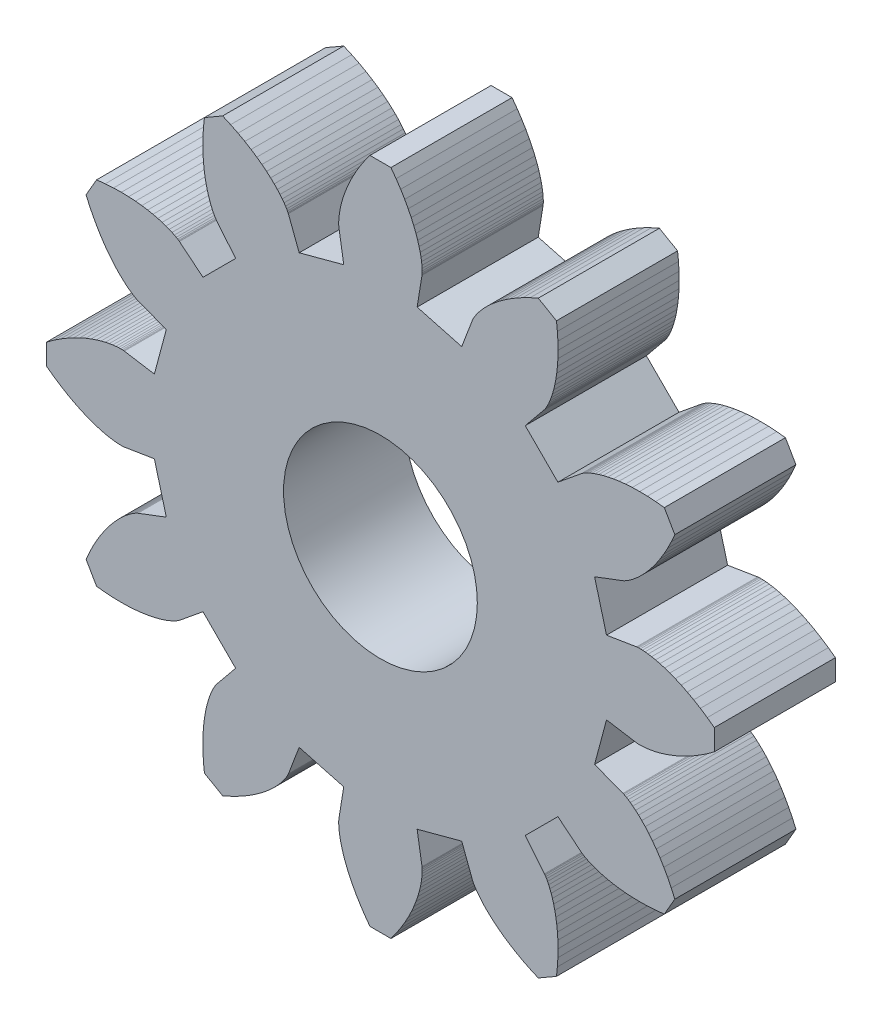
SolidWorks part; units mm, degrees
ref_plane "Front Plane" through (0, 0, 0) normal (0, 0, 1) x (1, 0, 0)
ref_plane "Top Plane" through (0, 0, 0) normal (0, 1, 0) x (1, 0, 0)
ref_plane "Right Plane" through (0, 0, 0) normal (1, 0, 0) x (0, 0, -1)
sketch "Model" plane through (0, 0, 0) normal (0, 0, 1) x (1, 0, 0)
  line L0 (9.3334, 1.5146) -> (10.5736, 1.7159)
  line L1 (10.5736, 1.7159) -> (10.5833, 1.7172)
  line L2 (10.5833, 1.7172) -> (10.6124, 1.7199)
  line L3 (10.6124, 1.7199) -> (10.6611, 1.7225)
  line L4 (10.6611, 1.7225) -> (10.7293, 1.7232)
  line L5 (10.7293, 1.7232) -> (10.817, 1.7204)
  line L6 (10.817, 1.7204) -> (10.9239, 1.7124)
  line L7 (10.9239, 1.7124) -> (11.0498, 1.6976)
  line L8 (11.0498, 1.6976) -> (11.1941, 1.6744)
  line L9 (11.1941, 1.6744) -> (11.3565, 1.6411)
  line L10 (11.3565, 1.6411) -> (11.5362, 1.5962)
  line L11 (11.5362, 1.5962) -> (11.7325, 1.5382)
  line L12 (11.7325, 1.5382) -> (11.9446, 1.4655)
  line L13 (11.9446, 1.4655) -> (12.1716, 1.3768)
  line L14 (12.1716, 1.3768) -> (12.4124, 1.2706)
  line L15 (12.4124, 1.2706) -> (12.6659, 1.1456)
  line L16 (12.6659, 1.1456) -> (12.931, 1.0006)
  line L17 (12.931, 1.0006) -> (13.2064, 0.8343)
  line L18 (13.2064, 0.8343) -> (13.4907, 0.6456)
  line L19 (13.4907, 0.6456) -> (13.7824, 0.4335)
  line L20 (13.7824, 0.4335) -> (13.7824, -0.4335)
  line L21 (13.7824, -0.4335) -> (13.4907, -0.6456)
  line L22 (13.4907, -0.6456) -> (13.2064, -0.8343)
  line L23 (13.2064, -0.8343) -> (12.931, -1.0006)
  line L24 (12.931, -1.0006) -> (12.6659, -1.1456)
  line L25 (12.6659, -1.1456) -> (12.4124, -1.2706)
  line L26 (12.4124, -1.2706) -> (12.1716, -1.3768)
  line L27 (12.1716, -1.3768) -> (11.9446, -1.4655)
  line L28 (11.9446, -1.4655) -> (11.7325, -1.5382)
  line L29 (11.7325, -1.5382) -> (11.5362, -1.5962)
  line L30 (11.5362, -1.5962) -> (11.3565, -1.6411)
  line L31 (11.3565, -1.6411) -> (11.1941, -1.6744)
  line L32 (11.1941, -1.6744) -> (11.0498, -1.6976)
  line L33 (11.0498, -1.6976) -> (10.9239, -1.7124)
  line L34 (10.9239, -1.7124) -> (10.817, -1.7204)
  line L35 (10.817, -1.7204) -> (10.7293, -1.7232)
  line L36 (10.7293, -1.7232) -> (10.6611, -1.7225)
  line L37 (10.6611, -1.7225) -> (10.6124, -1.7199)
  line L38 (10.6124, -1.7199) -> (10.5833, -1.7172)
  line L39 (10.5833, -1.7172) -> (10.5736, -1.7159)
  line L40 (10.5736, -1.7159) -> (9.3334, -1.5146)
  line L41 (9.3334, -1.5146) -> (8.8402, -3.355)
  line L42 (8.8402, -3.355) -> (10.015, -3.8008)
  line L43 (10.015, -3.8008) -> (10.024, -3.8045)
  line L44 (10.024, -3.8045) -> (10.0506, -3.8167)
  line L45 (10.0506, -3.8167) -> (10.094, -3.8388)
  line L46 (10.094, -3.8388) -> (10.1535, -3.8723)
  line L47 (10.1535, -3.8723) -> (10.228, -3.9186)
  line L48 (10.228, -3.9186) -> (10.3166, -3.979)
  line L49 (10.3166, -3.979) -> (10.4182, -4.0547)
  line L50 (10.4182, -4.0547) -> (10.5316, -4.147)
  line L51 (10.5316, -4.147) -> (10.6556, -4.257)
  line L52 (10.6556, -4.257) -> (10.7887, -4.3857)
  line L53 (10.7887, -4.3857) -> (10.9297, -4.5341)
  line L54 (10.9297, -4.5341) -> (11.0771, -4.7031)
  line L55 (11.0771, -4.7031) -> (11.2293, -4.8934)
  line L56 (11.2293, -4.8934) -> (11.3847, -5.1058)
  line L57 (11.3847, -5.1058) -> (11.5418, -5.3408)
  line L58 (11.5418, -5.3408) -> (11.6989, -5.599)
  line L59 (11.6989, -5.599) -> (11.8542, -5.8807)
  line L60 (11.8542, -5.8807) -> (12.0061, -6.1862)
  line L61 (12.0061, -6.1862) -> (12.1527, -6.5158)
  line L62 (12.1527, -6.5158) -> (11.7192, -7.2667)
  line L63 (11.7192, -7.2667) -> (11.3605, -7.3044)
  line L64 (11.3605, -7.3044) -> (11.0199, -7.3257)
  line L65 (11.0199, -7.3257) -> (10.6983, -7.332)
  line L66 (10.6983, -7.332) -> (10.3962, -7.3251)
  line L67 (10.3962, -7.3251) -> (10.1141, -7.3066)
  line L68 (10.1141, -7.3066) -> (9.8525, -7.2781)
  line L69 (9.8525, -7.2781) -> (9.6115, -7.2415)
  line L70 (9.6115, -7.2415) -> (9.3915, -7.1984)
  line L71 (9.3915, -7.1984) -> (9.1925, -7.1505)
  line L72 (9.1925, -7.1505) -> (9.0144, -7.0995)
  line L73 (9.0144, -7.0995) -> (8.8572, -7.0472)
  line L74 (8.8572, -7.0472) -> (8.7206, -6.9951)
  line L75 (8.7206, -6.9951) -> (8.6042, -6.945)
  line L76 (8.6042, -6.945) -> (8.5076, -6.8984)
  line L77 (8.5076, -6.8984) -> (8.4303, -6.857)
  line L78 (8.4303, -6.857) -> (8.3715, -6.8223)
  line L79 (8.3715, -6.8223) -> (8.3307, -6.7957)
  line L80 (8.3307, -6.7957) -> (8.3068, -6.7787)
  line L81 (8.3068, -6.7787) -> (8.2991, -6.7728)
  line L82 (8.2991, -6.7728) -> (7.3256, -5.9784)
  line L83 (7.3256, -5.9784) -> (5.9784, -7.3256)
  line L84 (5.9784, -7.3256) -> (6.7728, -8.2991)
  line L85 (6.7728, -8.2991) -> (6.7787, -8.3068)
  line L86 (6.7787, -8.3068) -> (6.7957, -8.3307)
  line L87 (6.7957, -8.3307) -> (6.8223, -8.3715)
  line L88 (6.8223, -8.3715) -> (6.857, -8.4303)
  line L89 (6.857, -8.4303) -> (6.8984, -8.5076)
  line L90 (6.8984, -8.5076) -> (6.945, -8.6042)
  line L91 (6.945, -8.6042) -> (6.9951, -8.7206)
  line L92 (6.9951, -8.7206) -> (7.0472, -8.8572)
  line L93 (7.0472, -8.8572) -> (7.0995, -9.0144)
  line L94 (7.0995, -9.0144) -> (7.1505, -9.1925)
  line L95 (7.1505, -9.1925) -> (7.1984, -9.3915)
  line L96 (7.1984, -9.3915) -> (7.2415, -9.6115)
  line L97 (7.2415, -9.6115) -> (7.2781, -9.8525)
  line L98 (7.2781, -9.8525) -> (7.3066, -10.1141)
  line L99 (7.3066, -10.1141) -> (7.3251, -10.3962)
  line L100 (7.3251, -10.3962) -> (7.332, -10.6983)
  line L101 (7.332, -10.6983) -> (7.3257, -11.0199)
  line L102 (7.3257, -11.0199) -> (7.3044, -11.3605)
  line L103 (7.3044, -11.3605) -> (7.2667, -11.7192)
  line L104 (7.2667, -11.7192) -> (6.5158, -12.1527)
  line L105 (6.5158, -12.1527) -> (6.1862, -12.0061)
  line L106 (6.1862, -12.0061) -> (5.8807, -11.8542)
  line L107 (5.8807, -11.8542) -> (5.599, -11.6989)
  line L108 (5.599, -11.6989) -> (5.3408, -11.5418)
  line L109 (5.3408, -11.5418) -> (5.1058, -11.3847)
  line L110 (5.1058, -11.3847) -> (4.8934, -11.2293)
  line L111 (4.8934, -11.2293) -> (4.7031, -11.0771)
  line L112 (4.7031, -11.0771) -> (4.5341, -10.9297)
  line L113 (4.5341, -10.9297) -> (4.3857, -10.7887)
  line L114 (4.3857, -10.7887) -> (4.257, -10.6556)
  line L115 (4.257, -10.6556) -> (4.147, -10.5316)
  line L116 (4.147, -10.5316) -> (4.0547, -10.4182)
  line L117 (4.0547, -10.4182) -> (3.979, -10.3166)
  line L118 (3.979, -10.3166) -> (3.9186, -10.228)
  line L119 (3.9186, -10.228) -> (3.8723, -10.1535)
  line L120 (3.8723, -10.1535) -> (3.8388, -10.094)
  line L121 (3.8388, -10.094) -> (3.8167, -10.0506)
  line L122 (3.8167, -10.0506) -> (3.8045, -10.024)
  line L123 (3.8045, -10.024) -> (3.8008, -10.015)
  line L124 (3.8008, -10.015) -> (3.355, -8.8402)
  line L125 (3.355, -8.8402) -> (1.5146, -9.3334)
  line L126 (1.5146, -9.3334) -> (1.7159, -10.5736)
  line L127 (1.7159, -10.5736) -> (1.7172, -10.5833)
  line L128 (1.7172, -10.5833) -> (1.7199, -10.6124)
  line L129 (1.7199, -10.6124) -> (1.7225, -10.6611)
  line L130 (1.7225, -10.6611) -> (1.7232, -10.7293)
  line L131 (1.7232, -10.7293) -> (1.7204, -10.817)
  line L132 (1.7204, -10.817) -> (1.7124, -10.9239)
  line L133 (1.7124, -10.9239) -> (1.6976, -11.0498)
  line L134 (1.6976, -11.0498) -> (1.6744, -11.1941)
  line L135 (1.6744, -11.1941) -> (1.6411, -11.3565)
  line L136 (1.6411, -11.3565) -> (1.5962, -11.5362)
  line L137 (1.5962, -11.5362) -> (1.5382, -11.7325)
  line L138 (1.5382, -11.7325) -> (1.4655, -11.9446)
  line L139 (1.4655, -11.9446) -> (1.3768, -12.1716)
  line L140 (1.3768, -12.1716) -> (1.2706, -12.4124)
  line L141 (1.2706, -12.4124) -> (1.1456, -12.6659)
  line L142 (1.1456, -12.6659) -> (1.0006, -12.931)
  line L143 (1.0006, -12.931) -> (0.8343, -13.2064)
  line L144 (0.8343, -13.2064) -> (0.6456, -13.4907)
  line L145 (0.6456, -13.4907) -> (0.4335, -13.7824)
  line L146 (0.4335, -13.7824) -> (-0.4335, -13.7824)
  line L147 (-0.4335, -13.7824) -> (-0.6456, -13.4907)
  line L148 (-0.6456, -13.4907) -> (-0.8343, -13.2064)
  line L149 (-0.8343, -13.2064) -> (-1.0006, -12.931)
  line L150 (-1.0006, -12.931) -> (-1.1456, -12.6659)
  line L151 (-1.1456, -12.6659) -> (-1.2706, -12.4124)
  line L152 (-1.2706, -12.4124) -> (-1.3768, -12.1716)
  line L153 (-1.3768, -12.1716) -> (-1.4655, -11.9446)
  line L154 (-1.4655, -11.9446) -> (-1.5382, -11.7325)
  line L155 (-1.5382, -11.7325) -> (-1.5962, -11.5362)
  line L156 (-1.5962, -11.5362) -> (-1.6411, -11.3565)
  line L157 (-1.6411, -11.3565) -> (-1.6744, -11.1941)
  line L158 (-1.6744, -11.1941) -> (-1.6976, -11.0498)
  line L159 (-1.6976, -11.0498) -> (-1.7124, -10.9239)
  line L160 (-1.7124, -10.9239) -> (-1.7204, -10.817)
  line L161 (-1.7204, -10.817) -> (-1.7232, -10.7293)
  line L162 (-1.7232, -10.7293) -> (-1.7225, -10.6611)
  line L163 (-1.7225, -10.6611) -> (-1.7199, -10.6124)
  line L164 (-1.7199, -10.6124) -> (-1.7172, -10.5833)
  line L165 (-1.7172, -10.5833) -> (-1.7159, -10.5736)
  line L166 (-1.7159, -10.5736) -> (-1.5146, -9.3334)
  line L167 (-1.5146, -9.3334) -> (-3.355, -8.8402)
  line L168 (-3.355, -8.8402) -> (-3.8008, -10.015)
  line L169 (-3.8008, -10.015) -> (-3.8045, -10.024)
  line L170 (-3.8045, -10.024) -> (-3.8167, -10.0506)
  line L171 (-3.8167, -10.0506) -> (-3.8388, -10.094)
  line L172 (-3.8388, -10.094) -> (-3.8723, -10.1535)
  line L173 (-3.8723, -10.1535) -> (-3.9186, -10.228)
  line L174 (-3.9186, -10.228) -> (-3.979, -10.3166)
  line L175 (-3.979, -10.3166) -> (-4.0547, -10.4182)
  line L176 (-4.0547, -10.4182) -> (-4.147, -10.5316)
  line L177 (-4.147, -10.5316) -> (-4.257, -10.6556)
  line L178 (-4.257, -10.6556) -> (-4.3857, -10.7887)
  line L179 (-4.3857, -10.7887) -> (-4.5341, -10.9297)
  line L180 (-4.5341, -10.9297) -> (-4.7031, -11.0771)
  line L181 (-4.7031, -11.0771) -> (-4.8934, -11.2293)
  line L182 (-4.8934, -11.2293) -> (-5.1058, -11.3847)
  line L183 (-5.1058, -11.3847) -> (-5.3408, -11.5418)
  line L184 (-5.3408, -11.5418) -> (-5.599, -11.6989)
  line L185 (-5.599, -11.6989) -> (-5.8807, -11.8542)
  line L186 (-5.8807, -11.8542) -> (-6.1862, -12.0061)
  line L187 (-6.1862, -12.0061) -> (-6.5158, -12.1527)
  line L188 (-6.5158, -12.1527) -> (-7.2667, -11.7192)
  line L189 (-7.2667, -11.7192) -> (-7.3044, -11.3605)
  line L190 (-7.3044, -11.3605) -> (-7.3257, -11.0199)
  line L191 (-7.3257, -11.0199) -> (-7.332, -10.6983)
  line L192 (-7.332, -10.6983) -> (-7.3251, -10.3962)
  line L193 (-7.3251, -10.3962) -> (-7.3066, -10.1141)
  line L194 (-7.3066, -10.1141) -> (-7.2781, -9.8525)
  line L195 (-7.2781, -9.8525) -> (-7.2415, -9.6115)
  line L196 (-7.2415, -9.6115) -> (-7.1984, -9.3915)
  line L197 (-7.1984, -9.3915) -> (-7.1505, -9.1925)
  line L198 (-7.1505, -9.1925) -> (-7.0995, -9.0144)
  line L199 (-7.0995, -9.0144) -> (-7.0472, -8.8572)
  line L200 (-7.0472, -8.8572) -> (-6.9951, -8.7206)
  line L201 (-6.9951, -8.7206) -> (-6.945, -8.6042)
  line L202 (-6.945, -8.6042) -> (-6.8984, -8.5076)
  line L203 (-6.8984, -8.5076) -> (-6.857, -8.4303)
  line L204 (-6.857, -8.4303) -> (-6.8223, -8.3715)
  line L205 (-6.8223, -8.3715) -> (-6.7957, -8.3307)
  line L206 (-6.7957, -8.3307) -> (-6.7787, -8.3068)
  line L207 (-6.7787, -8.3068) -> (-6.7728, -8.2991)
  line L208 (-6.7728, -8.2991) -> (-5.9784, -7.3256)
  line L209 (-5.9784, -7.3256) -> (-7.3256, -5.9784)
  line L210 (-7.3256, -5.9784) -> (-8.2991, -6.7728)
  line L211 (-8.2991, -6.7728) -> (-8.3068, -6.7787)
  line L212 (-8.3068, -6.7787) -> (-8.3307, -6.7957)
  line L213 (-8.3307, -6.7957) -> (-8.3715, -6.8223)
  line L214 (-8.3715, -6.8223) -> (-8.4303, -6.857)
  line L215 (-8.4303, -6.857) -> (-8.5076, -6.8984)
  line L216 (-8.5076, -6.8984) -> (-8.6042, -6.945)
  line L217 (-8.6042, -6.945) -> (-8.7206, -6.9951)
  line L218 (-8.7206, -6.9951) -> (-8.8572, -7.0472)
  line L219 (-8.8572, -7.0472) -> (-9.0144, -7.0995)
  line L220 (-9.0144, -7.0995) -> (-9.1925, -7.1505)
  line L221 (-9.1925, -7.1505) -> (-9.3915, -7.1984)
  line L222 (-9.3915, -7.1984) -> (-9.6115, -7.2415)
  line L223 (-9.6115, -7.2415) -> (-9.8525, -7.2781)
  line L224 (-9.8525, -7.2781) -> (-10.1141, -7.3066)
  line L225 (-10.1141, -7.3066) -> (-10.3962, -7.3251)
  line L226 (-10.3962, -7.3251) -> (-10.6983, -7.332)
  line L227 (-10.6983, -7.332) -> (-11.0199, -7.3257)
  line L228 (-11.0199, -7.3257) -> (-11.3605, -7.3044)
  line L229 (-11.3605, -7.3044) -> (-11.7192, -7.2667)
  line L230 (-11.7192, -7.2667) -> (-12.1527, -6.5158)
  line L231 (-12.1527, -6.5158) -> (-12.0061, -6.1862)
  line L232 (-12.0061, -6.1862) -> (-11.8542, -5.8807)
  line L233 (-11.8542, -5.8807) -> (-11.6989, -5.599)
  line L234 (-11.6989, -5.599) -> (-11.5418, -5.3408)
  line L235 (-11.5418, -5.3408) -> (-11.3847, -5.1058)
  line L236 (-11.3847, -5.1058) -> (-11.2293, -4.8934)
  line L237 (-11.2293, -4.8934) -> (-11.0771, -4.7031)
  line L238 (-11.0771, -4.7031) -> (-10.9297, -4.5341)
  line L239 (-10.9297, -4.5341) -> (-10.7887, -4.3857)
  line L240 (-10.7887, -4.3857) -> (-10.6556, -4.257)
  line L241 (-10.6556, -4.257) -> (-10.5316, -4.147)
  line L242 (-10.5316, -4.147) -> (-10.4182, -4.0547)
  line L243 (-10.4182, -4.0547) -> (-10.3166, -3.979)
  line L244 (-10.3166, -3.979) -> (-10.228, -3.9186)
  line L245 (-10.228, -3.9186) -> (-10.1535, -3.8723)
  line L246 (-10.1535, -3.8723) -> (-10.094, -3.8388)
  line L247 (-10.094, -3.8388) -> (-10.0506, -3.8167)
  line L248 (-10.0506, -3.8167) -> (-10.024, -3.8045)
  line L249 (-10.024, -3.8045) -> (-10.015, -3.8008)
  line L250 (-10.015, -3.8008) -> (-8.8402, -3.355)
  line L251 (-8.8402, -3.355) -> (-9.3334, -1.5146)
  line L252 (-9.3334, -1.5146) -> (-10.5736, -1.7159)
  line L253 (-10.5736, -1.7159) -> (-10.5833, -1.7172)
  line L254 (-10.5833, -1.7172) -> (-10.6124, -1.7199)
  line L255 (-10.6124, -1.7199) -> (-10.6611, -1.7225)
  line L256 (-10.6611, -1.7225) -> (-10.7293, -1.7232)
  line L257 (-10.7293, -1.7232) -> (-10.817, -1.7204)
  line L258 (-10.817, -1.7204) -> (-10.9239, -1.7124)
  line L259 (-10.9239, -1.7124) -> (-11.0498, -1.6976)
  line L260 (-11.0498, -1.6976) -> (-11.1941, -1.6744)
  line L261 (-11.1941, -1.6744) -> (-11.3565, -1.6411)
  line L262 (-11.3565, -1.6411) -> (-11.5362, -1.5962)
  line L263 (-11.5362, -1.5962) -> (-11.7325, -1.5382)
  line L264 (-11.7325, -1.5382) -> (-11.9446, -1.4655)
  line L265 (-11.9446, -1.4655) -> (-12.1716, -1.3768)
  line L266 (-12.1716, -1.3768) -> (-12.4124, -1.2706)
  line L267 (-12.4124, -1.2706) -> (-12.6659, -1.1456)
  line L268 (-12.6659, -1.1456) -> (-12.931, -1.0006)
  line L269 (-12.931, -1.0006) -> (-13.2064, -0.8343)
  line L270 (-13.2064, -0.8343) -> (-13.4907, -0.6456)
  line L271 (-13.4907, -0.6456) -> (-13.7824, -0.4335)
  line L272 (-13.7824, -0.4335) -> (-13.7824, 0.4335)
  line L273 (-13.7824, 0.4335) -> (-13.4907, 0.6456)
  line L274 (-13.4907, 0.6456) -> (-13.2064, 0.8343)
  line L275 (-13.2064, 0.8343) -> (-12.931, 1.0006)
  line L276 (-12.931, 1.0006) -> (-12.6659, 1.1456)
  line L277 (-12.6659, 1.1456) -> (-12.4124, 1.2706)
  line L278 (-12.4124, 1.2706) -> (-12.1716, 1.3768)
  line L279 (-12.1716, 1.3768) -> (-11.9446, 1.4655)
  line L280 (-11.9446, 1.4655) -> (-11.7325, 1.5382)
  line L281 (-11.7325, 1.5382) -> (-11.5362, 1.5962)
  line L282 (-11.5362, 1.5962) -> (-11.3565, 1.6411)
  line L283 (-11.3565, 1.6411) -> (-11.1941, 1.6744)
  line L284 (-11.1941, 1.6744) -> (-11.0498, 1.6976)
  line L285 (-11.0498, 1.6976) -> (-10.9239, 1.7124)
  line L286 (-10.9239, 1.7124) -> (-10.817, 1.7204)
  line L287 (-10.817, 1.7204) -> (-10.7293, 1.7232)
  line L288 (-10.7293, 1.7232) -> (-10.6611, 1.7225)
  line L289 (-10.6611, 1.7225) -> (-10.6124, 1.7199)
  line L290 (-10.6124, 1.7199) -> (-10.5833, 1.7172)
  line L291 (-10.5833, 1.7172) -> (-10.5736, 1.7159)
  line L292 (-10.5736, 1.7159) -> (-9.3334, 1.5146)
  line L293 (-9.3334, 1.5146) -> (-8.8402, 3.355)
  line L294 (-8.8402, 3.355) -> (-10.015, 3.8008)
  line L295 (-10.015, 3.8008) -> (-10.024, 3.8045)
  line L296 (-10.024, 3.8045) -> (-10.0506, 3.8167)
  line L297 (-10.0506, 3.8167) -> (-10.094, 3.8388)
  line L298 (-10.094, 3.8388) -> (-10.1535, 3.8723)
  line L299 (-10.1535, 3.8723) -> (-10.228, 3.9186)
  line L300 (-10.228, 3.9186) -> (-10.3166, 3.979)
  line L301 (-10.3166, 3.979) -> (-10.4182, 4.0547)
  line L302 (-10.4182, 4.0547) -> (-10.5316, 4.147)
  line L303 (-10.5316, 4.147) -> (-10.6556, 4.257)
  line L304 (-10.6556, 4.257) -> (-10.7887, 4.3857)
  line L305 (-10.7887, 4.3857) -> (-10.9297, 4.5341)
  line L306 (-10.9297, 4.5341) -> (-11.0771, 4.7031)
  line L307 (-11.0771, 4.7031) -> (-11.2293, 4.8934)
  line L308 (-11.2293, 4.8934) -> (-11.3847, 5.1058)
  line L309 (-11.3847, 5.1058) -> (-11.5418, 5.3408)
  line L310 (-11.5418, 5.3408) -> (-11.6989, 5.599)
  line L311 (-11.6989, 5.599) -> (-11.8542, 5.8807)
  line L312 (-11.8542, 5.8807) -> (-12.0061, 6.1862)
  line L313 (-12.0061, 6.1862) -> (-12.1527, 6.5158)
  line L314 (-12.1527, 6.5158) -> (-11.7192, 7.2667)
  line L315 (-11.7192, 7.2667) -> (-11.3605, 7.3044)
  line L316 (-11.3605, 7.3044) -> (-11.0199, 7.3257)
  line L317 (-11.0199, 7.3257) -> (-10.6983, 7.332)
  line L318 (-10.6983, 7.332) -> (-10.3962, 7.3251)
  line L319 (-10.3962, 7.3251) -> (-10.1141, 7.3066)
  line L320 (-10.1141, 7.3066) -> (-9.8525, 7.2781)
  line L321 (-9.8525, 7.2781) -> (-9.6115, 7.2415)
  line L322 (-9.6115, 7.2415) -> (-9.3915, 7.1984)
  line L323 (-9.3915, 7.1984) -> (-9.1925, 7.1505)
  line L324 (-9.1925, 7.1505) -> (-9.0144, 7.0995)
  line L325 (-9.0144, 7.0995) -> (-8.8572, 7.0472)
  line L326 (-8.8572, 7.0472) -> (-8.7206, 6.9951)
  line L327 (-8.7206, 6.9951) -> (-8.6042, 6.945)
  line L328 (-8.6042, 6.945) -> (-8.5076, 6.8984)
  line L329 (-8.5076, 6.8984) -> (-8.4303, 6.857)
  line L330 (-8.4303, 6.857) -> (-8.3715, 6.8223)
  line L331 (-8.3715, 6.8223) -> (-8.3307, 6.7957)
  line L332 (-8.3307, 6.7957) -> (-8.3068, 6.7787)
  line L333 (-8.3068, 6.7787) -> (-8.2991, 6.7728)
  line L334 (-8.2991, 6.7728) -> (-7.3256, 5.9784)
  line L335 (-7.3256, 5.9784) -> (-5.9784, 7.3256)
  line L336 (-5.9784, 7.3256) -> (-6.7728, 8.2991)
  line L337 (-6.7728, 8.2991) -> (-6.7787, 8.3068)
  line L338 (-6.7787, 8.3068) -> (-6.7957, 8.3307)
  line L339 (-6.7957, 8.3307) -> (-6.8223, 8.3715)
  line L340 (-6.8223, 8.3715) -> (-6.857, 8.4303)
  line L341 (-6.857, 8.4303) -> (-6.8984, 8.5076)
  line L342 (-6.8984, 8.5076) -> (-6.945, 8.6042)
  line L343 (-6.945, 8.6042) -> (-6.9951, 8.7206)
  line L344 (-6.9951, 8.7206) -> (-7.0472, 8.8572)
  line L345 (-7.0472, 8.8572) -> (-7.0995, 9.0144)
  line L346 (-7.0995, 9.0144) -> (-7.1505, 9.1925)
  line L347 (-7.1505, 9.1925) -> (-7.1984, 9.3915)
  line L348 (-7.1984, 9.3915) -> (-7.2415, 9.6115)
  line L349 (-7.2415, 9.6115) -> (-7.2781, 9.8525)
  line L350 (-7.2781, 9.8525) -> (-7.3066, 10.1141)
  line L351 (-7.3066, 10.1141) -> (-7.3251, 10.3962)
  line L352 (-7.3251, 10.3962) -> (-7.332, 10.6983)
  line L353 (-7.332, 10.6983) -> (-7.3257, 11.0199)
  line L354 (-7.3257, 11.0199) -> (-7.3044, 11.3605)
  line L355 (-7.3044, 11.3605) -> (-7.2667, 11.7192)
  line L356 (-7.2667, 11.7192) -> (-6.5158, 12.1527)
  line L357 (-6.5158, 12.1527) -> (-6.1862, 12.0061)
  line L358 (-6.1862, 12.0061) -> (-5.8807, 11.8542)
  line L359 (-5.8807, 11.8542) -> (-5.599, 11.6989)
  line L360 (-5.599, 11.6989) -> (-5.3408, 11.5418)
  line L361 (-5.3408, 11.5418) -> (-5.1058, 11.3847)
  line L362 (-5.1058, 11.3847) -> (-4.8934, 11.2293)
  line L363 (-4.8934, 11.2293) -> (-4.7031, 11.0771)
  line L364 (-4.7031, 11.0771) -> (-4.5341, 10.9297)
  line L365 (-4.5341, 10.9297) -> (-4.3857, 10.7887)
  line L366 (-4.3857, 10.7887) -> (-4.257, 10.6556)
  line L367 (-4.257, 10.6556) -> (-4.147, 10.5316)
  line L368 (-4.147, 10.5316) -> (-4.0547, 10.4182)
  line L369 (-4.0547, 10.4182) -> (-3.979, 10.3166)
  line L370 (-3.979, 10.3166) -> (-3.9186, 10.228)
  line L371 (-3.9186, 10.228) -> (-3.8723, 10.1535)
  line L372 (-3.8723, 10.1535) -> (-3.8388, 10.094)
  line L373 (-3.8388, 10.094) -> (-3.8167, 10.0506)
  line L374 (-3.8167, 10.0506) -> (-3.8045, 10.024)
  line L375 (-3.8045, 10.024) -> (-3.8008, 10.015)
  line L376 (-3.8008, 10.015) -> (-3.355, 8.8402)
  line L377 (-3.355, 8.8402) -> (-1.5146, 9.3334)
  line L378 (-1.5146, 9.3334) -> (-1.7159, 10.5736)
  line L379 (-1.7159, 10.5736) -> (-1.7172, 10.5833)
  line L380 (-1.7172, 10.5833) -> (-1.7199, 10.6124)
  line L381 (-1.7199, 10.6124) -> (-1.7225, 10.6611)
  line L382 (-1.7225, 10.6611) -> (-1.7232, 10.7293)
  line L383 (-1.7232, 10.7293) -> (-1.7204, 10.817)
  line L384 (-1.7204, 10.817) -> (-1.7124, 10.9239)
  line L385 (-1.7124, 10.9239) -> (-1.6976, 11.0498)
  line L386 (-1.6976, 11.0498) -> (-1.6744, 11.1941)
  line L387 (-1.6744, 11.1941) -> (-1.6411, 11.3565)
  line L388 (-1.6411, 11.3565) -> (-1.5962, 11.5362)
  line L389 (-1.5962, 11.5362) -> (-1.5382, 11.7325)
  line L390 (-1.5382, 11.7325) -> (-1.4655, 11.9446)
  line L391 (-1.4655, 11.9446) -> (-1.3768, 12.1716)
  line L392 (-1.3768, 12.1716) -> (-1.2706, 12.4124)
  line L393 (-1.2706, 12.4124) -> (-1.1456, 12.6659)
  line L394 (-1.1456, 12.6659) -> (-1.0006, 12.931)
  line L395 (-1.0006, 12.931) -> (-0.8343, 13.2064)
  line L396 (-0.8343, 13.2064) -> (-0.6456, 13.4907)
  line L397 (-0.6456, 13.4907) -> (-0.4335, 13.7824)
  line L398 (-0.4335, 13.7824) -> (0.4335, 13.7824)
  line L399 (0.4335, 13.7824) -> (0.6456, 13.4907)
  line L400 (0.6456, 13.4907) -> (0.8343, 13.2064)
  line L401 (0.8343, 13.2064) -> (1.0006, 12.931)
  line L402 (1.0006, 12.931) -> (1.1456, 12.6659)
  line L403 (1.1456, 12.6659) -> (1.2706, 12.4124)
  line L404 (1.2706, 12.4124) -> (1.3768, 12.1716)
  line L405 (1.3768, 12.1716) -> (1.4655, 11.9446)
  line L406 (1.4655, 11.9446) -> (1.5382, 11.7325)
  line L407 (1.5382, 11.7325) -> (1.5962, 11.5362)
  line L408 (1.5962, 11.5362) -> (1.6411, 11.3565)
  line L409 (1.6411, 11.3565) -> (1.6744, 11.1941)
  line L410 (1.6744, 11.1941) -> (1.6976, 11.0498)
  line L411 (1.6976, 11.0498) -> (1.7124, 10.9239)
  line L412 (1.7124, 10.9239) -> (1.7204, 10.817)
  line L413 (1.7204, 10.817) -> (1.7232, 10.7293)
  line L414 (1.7232, 10.7293) -> (1.7225, 10.6611)
  line L415 (1.7225, 10.6611) -> (1.7199, 10.6124)
  line L416 (1.7199, 10.6124) -> (1.7172, 10.5833)
  line L417 (1.7172, 10.5833) -> (1.7159, 10.5736)
  line L418 (1.7159, 10.5736) -> (1.5146, 9.3334)
  line L419 (1.5146, 9.3334) -> (3.355, 8.8402)
  line L420 (3.355, 8.8402) -> (3.8008, 10.015)
  line L421 (3.8008, 10.015) -> (3.8045, 10.024)
  line L422 (3.8045, 10.024) -> (3.8167, 10.0506)
  line L423 (3.8167, 10.0506) -> (3.8388, 10.094)
  line L424 (3.8388, 10.094) -> (3.8723, 10.1535)
  line L425 (3.8723, 10.1535) -> (3.9186, 10.228)
  line L426 (3.9186, 10.228) -> (3.979, 10.3166)
  line L427 (3.979, 10.3166) -> (4.0547, 10.4182)
  line L428 (4.0547, 10.4182) -> (4.147, 10.5316)
  line L429 (4.147, 10.5316) -> (4.257, 10.6556)
  line L430 (4.257, 10.6556) -> (4.3857, 10.7887)
  line L431 (4.3857, 10.7887) -> (4.5341, 10.9297)
  line L432 (4.5341, 10.9297) -> (4.7031, 11.0771)
  line L433 (4.7031, 11.0771) -> (4.8934, 11.2293)
  line L434 (4.8934, 11.2293) -> (5.1058, 11.3847)
  line L435 (5.1058, 11.3847) -> (5.3408, 11.5418)
  line L436 (5.3408, 11.5418) -> (5.599, 11.6989)
  line L437 (5.599, 11.6989) -> (5.8807, 11.8542)
  line L438 (5.8807, 11.8542) -> (6.1862, 12.0061)
  line L439 (6.1862, 12.0061) -> (6.5158, 12.1527)
  line L440 (6.5158, 12.1527) -> (7.2667, 11.7192)
  line L441 (7.2667, 11.7192) -> (7.3044, 11.3605)
  line L442 (7.3044, 11.3605) -> (7.3257, 11.0199)
  line L443 (7.3257, 11.0199) -> (7.332, 10.6983)
  line L444 (7.332, 10.6983) -> (7.3251, 10.3962)
  line L445 (7.3251, 10.3962) -> (7.3066, 10.1141)
  line L446 (7.3066, 10.1141) -> (7.2781, 9.8525)
  line L447 (7.2781, 9.8525) -> (7.2415, 9.6115)
  line L448 (7.2415, 9.6115) -> (7.1984, 9.3915)
  line L449 (7.1984, 9.3915) -> (7.1505, 9.1925)
  line L450 (7.1505, 9.1925) -> (7.0995, 9.0144)
  line L451 (7.0995, 9.0144) -> (7.0472, 8.8572)
  line L452 (7.0472, 8.8572) -> (6.9951, 8.7206)
  line L453 (6.9951, 8.7206) -> (6.945, 8.6042)
  line L454 (6.945, 8.6042) -> (6.8984, 8.5076)
  line L455 (6.8984, 8.5076) -> (6.857, 8.4303)
  line L456 (6.857, 8.4303) -> (6.8223, 8.3715)
  line L457 (6.8223, 8.3715) -> (6.7957, 8.3307)
  line L458 (6.7957, 8.3307) -> (6.7787, 8.3068)
  line L459 (6.7787, 8.3068) -> (6.7728, 8.2991)
  line L460 (6.7728, 8.2991) -> (5.9784, 7.3256)
  line L461 (5.9784, 7.3256) -> (7.3256, 5.9784)
  line L462 (7.3256, 5.9784) -> (8.2991, 6.7728)
  line L463 (8.2991, 6.7728) -> (8.3068, 6.7787)
  line L464 (8.3068, 6.7787) -> (8.3307, 6.7957)
  line L465 (8.3307, 6.7957) -> (8.3715, 6.8223)
  line L466 (8.3715, 6.8223) -> (8.4303, 6.857)
  line L467 (8.4303, 6.857) -> (8.5076, 6.8984)
  line L468 (8.5076, 6.8984) -> (8.6042, 6.945)
  line L469 (8.6042, 6.945) -> (8.7206, 6.9951)
  line L470 (8.7206, 6.9951) -> (8.8572, 7.0472)
  line L471 (8.8572, 7.0472) -> (9.0144, 7.0995)
  line L472 (9.0144, 7.0995) -> (9.1925, 7.1505)
  line L473 (9.1925, 7.1505) -> (9.3915, 7.1984)
  line L474 (9.3915, 7.1984) -> (9.6115, 7.2415)
  line L475 (9.6115, 7.2415) -> (9.8525, 7.2781)
  line L476 (9.8525, 7.2781) -> (10.1141, 7.3066)
  line L477 (10.1141, 7.3066) -> (10.3962, 7.3251)
  line L478 (10.3962, 7.3251) -> (10.6983, 7.332)
  line L479 (10.6983, 7.332) -> (11.0199, 7.3257)
  line L480 (11.0199, 7.3257) -> (11.3605, 7.3044)
  line L481 (11.3605, 7.3044) -> (11.7192, 7.2667)
  line L482 (11.7192, 7.2667) -> (12.1527, 6.5158)
  line L483 (12.1527, 6.5158) -> (12.0061, 6.1862)
  line L484 (12.0061, 6.1862) -> (11.8542, 5.8807)
  line L485 (11.8542, 5.8807) -> (11.6989, 5.599)
  line L486 (11.6989, 5.599) -> (11.5418, 5.3408)
  line L487 (11.5418, 5.3408) -> (11.3847, 5.1058)
  line L488 (11.3847, 5.1058) -> (11.2293, 4.8934)
  line L489 (11.2293, 4.8934) -> (11.0771, 4.7031)
  line L490 (11.0771, 4.7031) -> (10.9297, 4.5341)
  line L491 (10.9297, 4.5341) -> (10.7887, 4.3857)
  line L492 (10.7887, 4.3857) -> (10.6556, 4.257)
  line L493 (10.6556, 4.257) -> (10.5316, 4.147)
  line L494 (10.5316, 4.147) -> (10.4182, 4.0547)
  line L495 (10.4182, 4.0547) -> (10.3166, 3.979)
  line L496 (10.3166, 3.979) -> (10.228, 3.9186)
  line L497 (10.228, 3.9186) -> (10.1535, 3.8723)
  line L498 (10.1535, 3.8723) -> (10.094, 3.8388)
  line L499 (10.094, 3.8388) -> (10.0506, 3.8167)
  line L500 (10.0506, 3.8167) -> (10.024, 3.8045)
  line L501 (10.024, 3.8045) -> (10.015, 3.8008)
  line L502 (10.015, 3.8008) -> (8.8402, 3.355)
  line L503 (8.8402, 3.355) -> (9.3334, 1.5146)
  circle A2 centre (0, 0) radius 4
  dimension "D1" = 8
extrude "Boss-Extrude3" add sketch "Model" along normal blind 5
